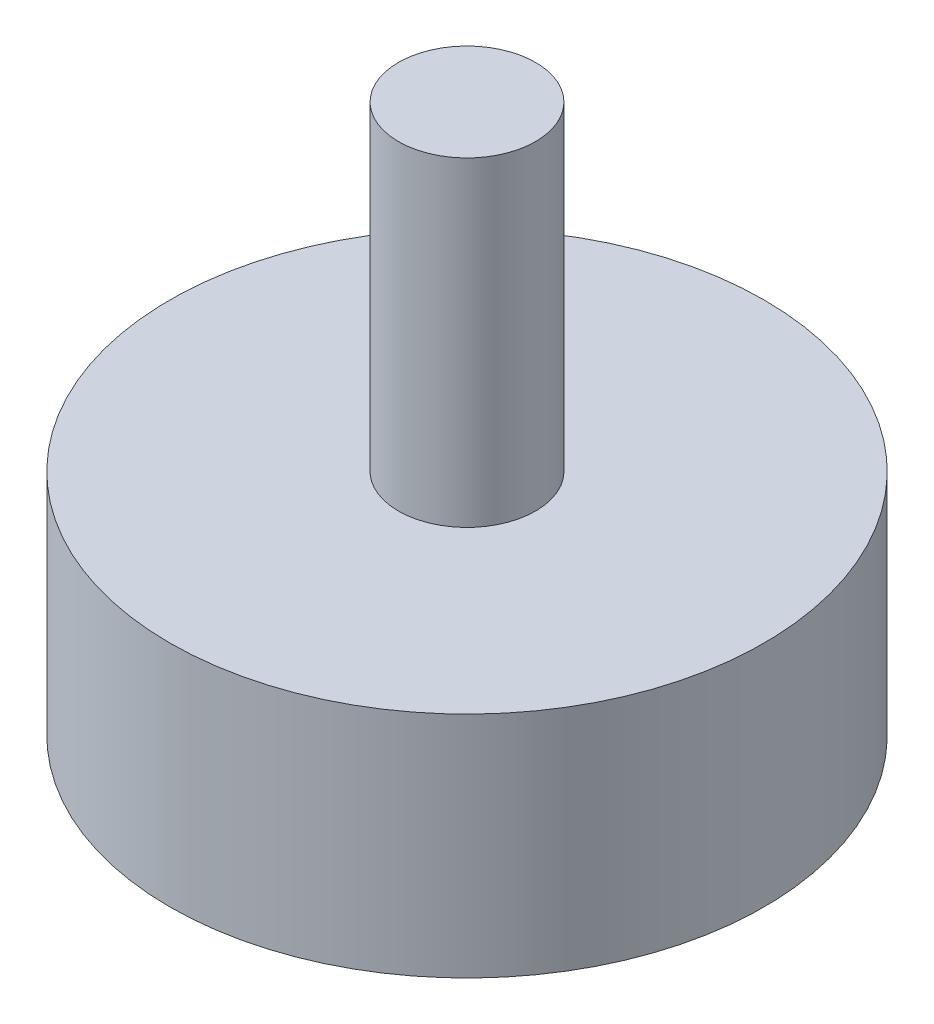
SolidWorks part; units mm, degrees
ref_plane "Front Plane" through (0, 0, 0) normal (0, 0, 1) x (1, 0, 0)
ref_plane "Top Plane" through (0, 0, 0) normal (0, 1, 0) x (1, 0, 0)
ref_plane "Right Plane" through (0, 0, 0) normal (1, 0, 0) x (0, 0, -1)
sketch "Skizze1" plane through (0, 0, 0) normal (0, 1, 0) x (1, 0, 0)
  circle A0 centre (0, 0) radius 6.5
  dimension "D1" = 13
extrude "Aufsatz-Linear austragen1" add sketch "Skizze1" along normal blind 5
sketch "Skizze2" plane through (0, 5, 0) normal (0, 1, 0) x (1, 0, 0)
  circle A0 centre (0, 0) radius 1.5
  dimension "D1" = 3
extrude "Aufsatz-Linear austragen2" add sketch "Skizze2" along normal blind 7
